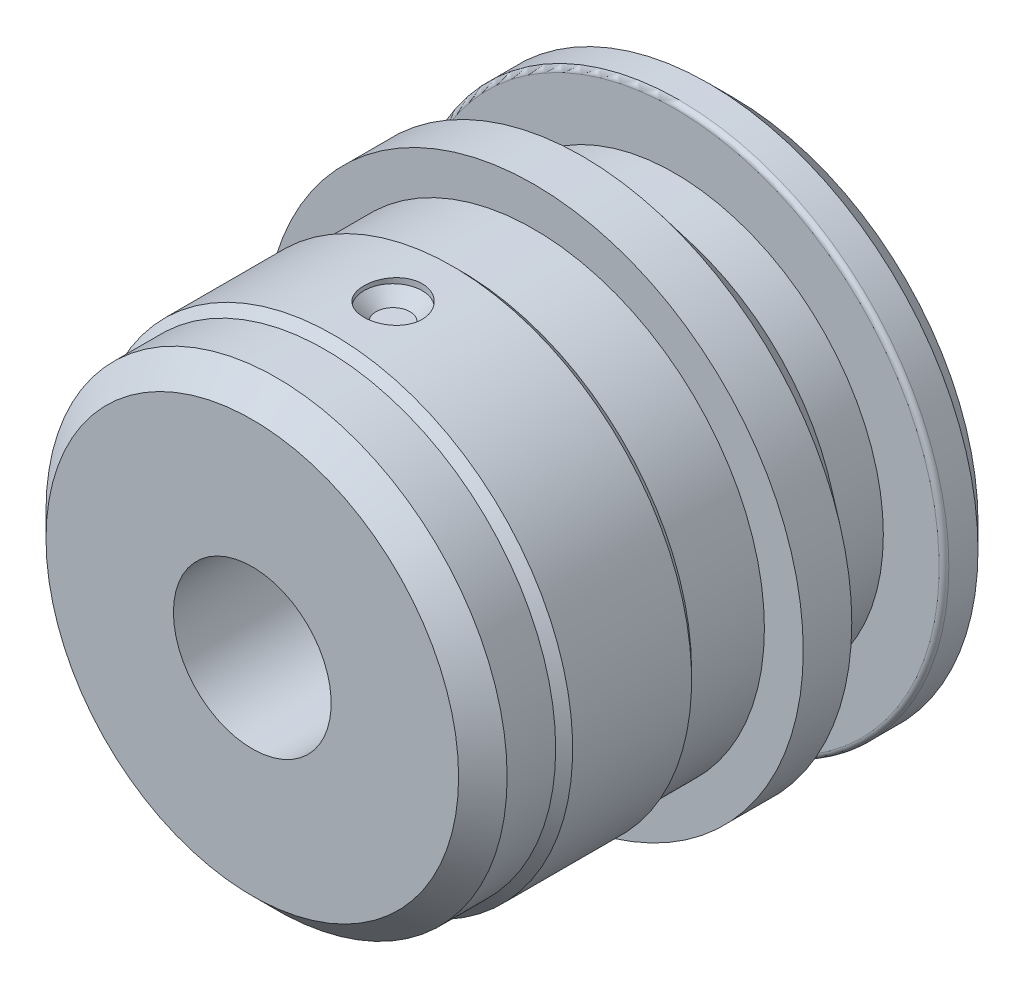
SolidWorks part; units mm, degrees
ref_plane "정면" through (0, 0, 0) normal (0, 0, 1) x (1, 0, 0)
ref_plane "윗면" through (0, 0, 0) normal (0, 1, 0) x (1, 0, 0)
ref_plane "우측면" through (0, 0, 0) normal (1, 0, 0) x (0, 0, -1)
sketch "스케치3" plane through (0, 0, 0) normal (0, 1, 0) x (1, 0, 0)
  line L0 (0, 0) -> (0, -21.8) construction
  line L1 (11.1, 0) -> (11.1, -2.4)
  line L2 (11.1, -2.4) -> (8.6, -2.4)
  line L3 (11.1, 0) -> (6.1, 0)
  line L4 (8.6, -2.4) -> (8.6, -4.2)
  line L5 (8.6, -4.2) -> (11.1, -6.2)
  line L6 (11.1, -6.2) -> (11.1, -8.2)
  line L7 (11.1, -8.2) -> (9.5, -8.2)
  line L8 (9.85, -16.45) -> (9.5, -16.8)
  line L10 (9.5, -8.2) -> (9.5, -11.2)
  line L12 (9.5, -19.8) -> (3.25, -19.8)
  line L13 (3.25, -19.8) -> (3.25, -11.8)
  line L14 (3.25, -11.8) -> (4.4, -11.8)
  line L15 (4.4, -11.8) -> (4.4, -10)
  line L16 (4.4, -10) -> (3.4, -10)
  line L17 (3.4, -10) -> (3.4, -8.5)
  line L18 (3.4, -8.5) -> (6.1, -7.7765)
  line L19 (6.1, -7.7765) -> (6.1, 0)
  line L20 (0, 0) -> (6.1, 0) construction
  line L21 (9.5, -11.2) -> (9.85, -11.55)
  line L34 (9.85, -11.55) -> (9.85, -16.45)
  line L37 (9.5, -16.8) -> (9.5, -19.8)
  dimension "D2" = 19
  dimension "D3" = 2.4
  dimension "D4" = 2
  dimension "D5" = 1.8
  dimension "D6" = 2
  dimension "D7" = 12.2
  dimension "D8" = 6.5
  dimension "D9" = 3
  dimension "D10" = 17.2
  dimension "D11" = 8
  dimension "D12" = 3
  dimension "D13" = 10
  dimension "D14" = 8.8
  dimension "D15" = 6.8
  dimension "D16" = 105
  dimension "D17" = 1.8
  dimension "D18" = 1.5
  dimension "D19" = 22.2
  dimension "D20" = 135
  dimension "D21" = 135
  dimension "D22" = 19.7
revolve "회전2" add sketch "스케치3" angle 360 about L0
chamfer "모따기1" distance 1 angle 45 2 edges at (-6.1, 0, 0) (-9.5, 0, 19.8)
chamfer "모따기2" distance 1 angle 45 1 edges at (-11.1, 0, 0)
fillet "필렛1" radius 0.2 1 edges at (-11.1, 0, 2.4)
ref_plane "평면1" through (0, 11.1, 0) normal (0, 1, 0) x (1, 0, 0)
sketch "스케치4" plane through (0, 11.1, 0) normal (0, 1, 0) x (1, 0, 0)
  line L0 (0, 0) -> (0, -14) construction
  line L1 (0, -14) -> (6, -14) construction
  circle A0 centre (6, -14) radius 1
  dimension "D1" = 2
  dimension "D2" = 6
  dimension "D3" = 14
extrude "컷-돌출1" [suppressed] cut sketch "스케치4" against normal blind 20
mirror "대칭 복사1" [suppressed] about plane through (0, 0, 0) normal (1, 0, 0)
sketch "스케치5" plane through (0, 11.1, 0) normal (0, 1, 0) x (1, 0, 0)
  line L0 (0, 0) -> (0, -14) construction
  line L1 (10.1, 0) -> (-10.1, 0) construction
  circle A0 centre (0, -14) radius 1.2
  dimension "D1" = 2.4
  dimension "D2" = 14
extrude "컷-돌출2" cut sketch "스케치5" against normal blind 2
chamfer "모따기3" distance 0.5 angle 45 1 edges at (0, 9.1, 15.2)
pattern_circular "원형 패턴1" count 2 over 360 about axis through (0, 0, 0) along (0, 0, -1) of "컷-돌출2", "모따기3"
